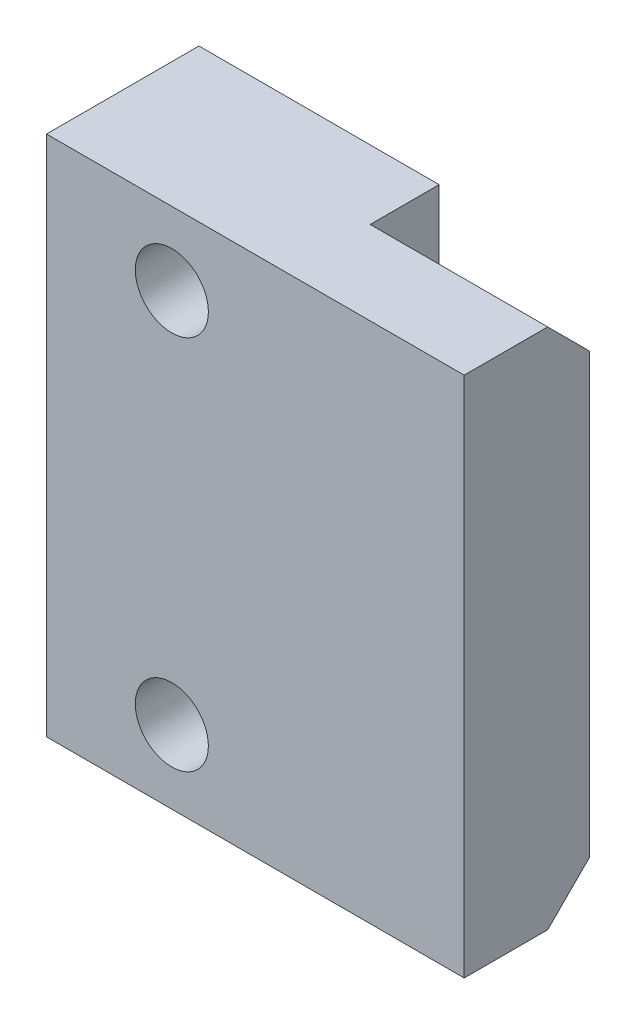
SolidWorks part; units mm, degrees
material "3D printed plastic"
ref_plane "Front Plane" through (0, 0, 0) normal (0, 0, 1) x (1, 0, 0)
ref_plane "Top Plane" through (0, 0, 0) normal (0, 1, 0) x (1, 0, 0)
ref_plane "Right Plane" through (0, 0, 0) normal (1, 0, 0) x (0, 0, -1)
sketch "Sketch1" plane through (0, 0, 0) normal (0, 1, 0) x (1, 0, 0)
  line L1 (-10, 7.3) -> (1.5, 7.3)
  line L2 (-10, 7.3) -> (-10, 0)
  line L3 (-10, 0) -> (10, 0)
  line L4 (10, 6) -> (10, 0)
  line L6 (1.5, 7.3) -> (1.5, 6)
  line L7 (1.5, 6) -> (10, 6)
  dimension "D1" = 1.3
  dimension "D2" = 11.5
  dimension "D3" = 20
  dimension "D4" = 6
extrude "Boss-Extrude1" add sketch "Sketch1" along normal mid plane 25
sketch "Sketch2" plane through (0, 0, 0) normal (0, 0, 1) x (1, 0, 0)
  line L0 (-4, 9) -> (-4, -9) construction
  line L1 (-4, 0) -> (-10, 0) construction
  line L2 (-10, 12.5) -> (-10, -12.5) construction
  circle A0 centre (-4, 9) radius 1.75
  circle A1 centre (-4, -9) radius 1.75
  dimension "D2" = 3.5
  dimension "D1" = 18
  dimension "D3" = 6
extrude "Cut-Extrude1" cut sketch "Sketch2" against normal through all
chamfer "Chamfer1" distance 2 angle 45 2 edges at (5.75, -12.5, -6) (5.75, 12.5, -6)
